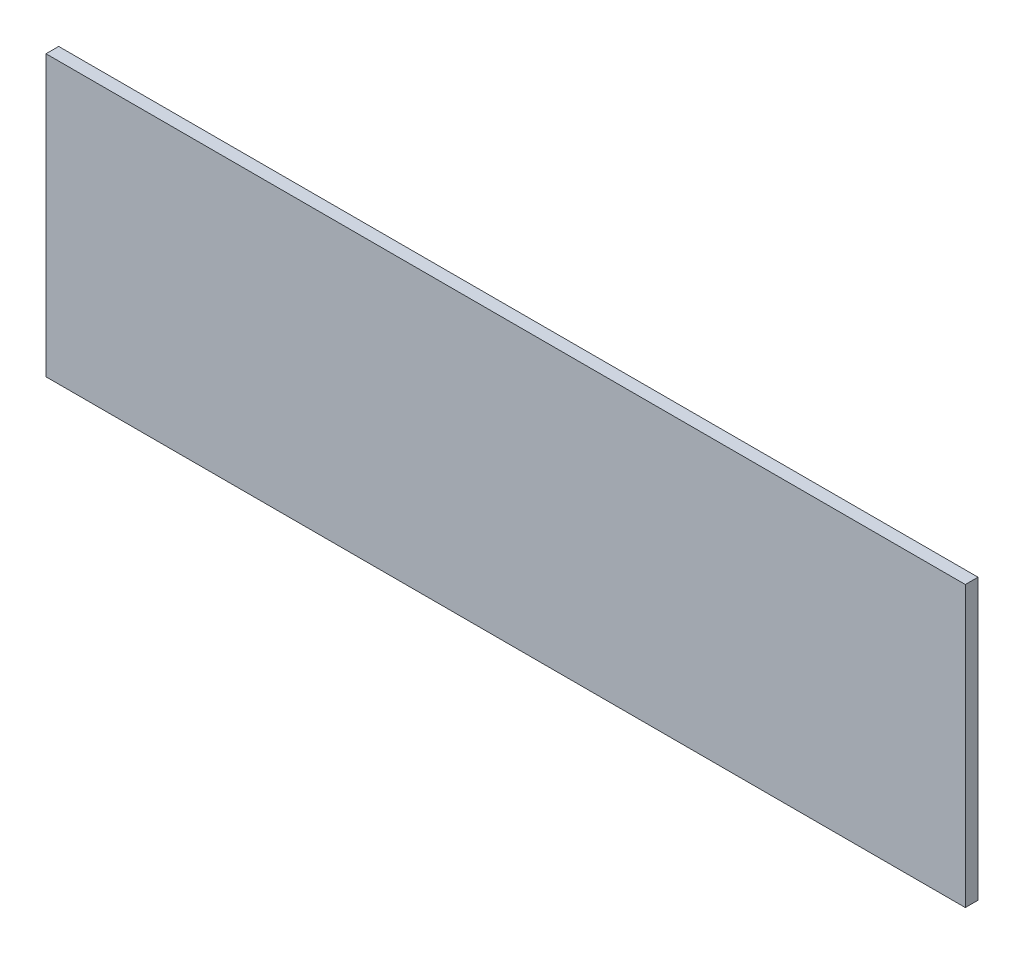
SolidWorks part; units mm, degrees
ref_plane "Front Plane" through (0, 0, 0) normal (0, 0, 1) x (1, 0, 0)
ref_plane "Top Plane" through (0, 0, 0) normal (0, 1, 0) x (1, 0, 0)
ref_plane "Right Plane" through (0, 0, 0) normal (1, 0, 0) x (0, 0, -1)
sketch "Sketch1" plane through (0, 0, 0) normal (0, 0, 1) x (1, 0, 0)
  line L1 (-230, -70) -> (230, -70)
  line L2 (-230, -70) -> (-230, 70)
  line L3 (-230, 70) -> (230, 70)
  line L4 (230, -70) -> (230, 70)
  line L5 (-230, -70) -> (230, 70) construction
  line L6 (-230, 70) -> (230, -70) construction
  point P0 (0, 0)
  dimension "D1" = 140
  dimension "D2" = 460
extrude "Boss-Extrude1" add sketch "Sketch1" along normal blind 6.35
